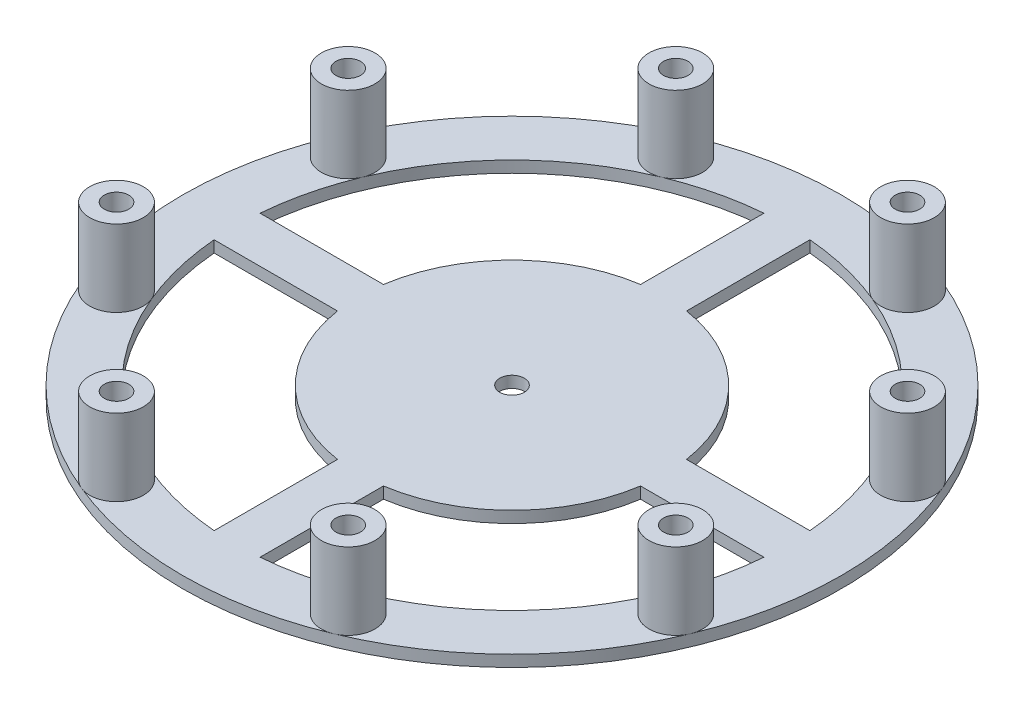
SolidWorks part; units mm, degrees
material "ABS"
ref_plane "Plano frontal" through (0, 0, 0) normal (0, 0, 1) x (1, 0, 0)
ref_plane "Plano superior" through (0, 0, 0) normal (0, 1, 0) x (1, 0, 0)
ref_plane "Plano direito" through (0, 0, 0) normal (1, 0, 0) x (0, 0, -1)
sketch "Esboço1" plane through (0, 0, 0) normal (0, 1, 0) x (1, 0, 0)
  line L0 (43, 0) -> (-43, 0) construction
  line L1 (0, 43) -> (0, -43) construction
  line L2 (0, 0) -> (-39.7268, 16.4554) construction
  line L3 (-3, 19.7737) -> (-3, 35.8748)
  line L4 (3, 19.7737) -> (3, 35.8748)
  line L5 (19.7737, 3) -> (35.8748, 3)
  line L6 (19.7737, -3) -> (35.8748, -3)
  line L7 (3, -19.7737) -> (3, -35.8748)
  line L8 (-3, -19.7737) -> (-3, -35.8748)
  line L9 (-19.7737, -3) -> (-35.8748, -3)
  line L10 (-19.7737, 3) -> (-35.8748, 3)
  circle A0 centre (0, 0) radius 43
  arc A1 (-3, 35.8748) -> (-35.8748, 3) centre (0, 0) ccw
  circle A2 centre (-36.4932, 15.116) radius 1.6
  circle A3 centre (-15.116, 36.4932) radius 1.6
  circle A4 centre (15.116, 36.4932) radius 1.6
  circle A5 centre (36.4932, 15.116) radius 1.6
  circle A6 centre (36.4932, -15.116) radius 1.6
  circle A7 centre (15.116, -36.4932) radius 1.6
  circle A8 centre (-15.116, -36.4932) radius 1.6
  circle A9 centre (-36.4932, -15.116) radius 1.6
  arc A10 (-3, 19.7737) -> (-19.7737, 3) centre (0, 0) ccw
  arc A11 (19.7737, 3) -> (3, 19.7737) centre (0, 0) ccw
  arc A12 (3, -19.7737) -> (19.7737, -3) centre (0, 0) ccw
  arc A13 (-19.7737, -3) -> (-3, -19.7737) centre (0, 0) ccw
  arc A14 (35.8748, 3) -> (3, 35.8748) centre (0, 0) ccw
  arc A15 (3, -35.8748) -> (35.8748, -3) centre (0, 0) ccw
  arc A16 (-35.8748, -3) -> (-3, -35.8748) centre (0, 0) ccw
  circle A17 centre (0, 0) radius 1.6
  point P28 (0, 0)
  point P46 (0, 0)
  dimension "D1" = 86
  dimension "D2" = 7
  dimension "D4" = 3.2
  dimension "D7" = 40
  dimension "D10" = 3.2
  dimension "D3" = 22.5
  dimension "D5" = 39.5
  dimension "D8" = 3
  dimension "D6" = 8
  dimension "D9" = 4
extrude "Ressalto-extrusão1" add sketch "Esboço1" along normal mid plane 1.5
sketch "Esboço2" plane through (0, 0.75, 0) normal (0, 1, 0) x (1, 0, 0)
  circle A0 centre (-15.116, 36.4932) radius 3.5
  circle A1 centre (-15.116, 36.4932) radius 1.6
  circle A2 centre (15.116, 36.4932) radius 3.5
  circle A3 centre (15.116, 36.4932) radius 1.6
  circle A4 centre (36.4932, 15.116) radius 3.5
  circle A5 centre (36.4932, 15.116) radius 1.6
  circle A6 centre (36.4932, -15.116) radius 3.5
  circle A7 centre (36.4932, -15.116) radius 1.6
  circle A8 centre (15.116, -36.4932) radius 3.5
  circle A9 centre (15.116, -36.4932) radius 1.6
  circle A10 centre (-15.116, -36.4932) radius 3.5
  circle A11 centre (-15.116, -36.4932) radius 1.6
  circle A12 centre (-36.4932, -15.116) radius 3.5
  circle A13 centre (-36.4932, -15.116) radius 1.6
  circle A14 centre (-36.4932, 15.116) radius 3.5
  circle A15 centre (-36.4932, 15.116) radius 1.6
  point P28 (0, 0)
  dimension "D1" = 7
  dimension "D2" = 3.2
  dimension "D3" = 8
extrude "Ressalto-extrusão3" add sketch "Esboço2" along normal blind 10
